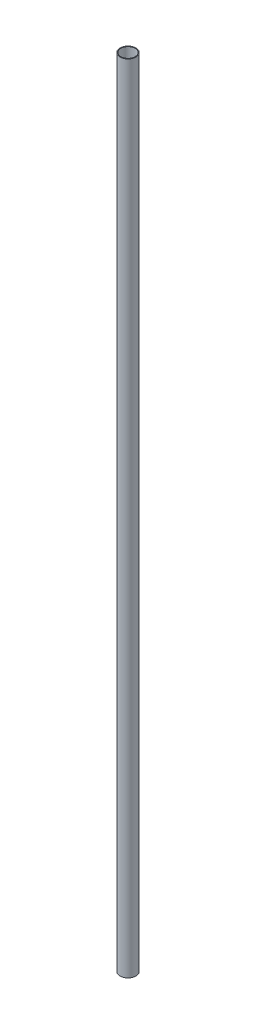
SolidWorks part; units mm, degrees
material "Thornel Mat VMA"
ref_plane "前视基准面" through (0, 0, 0) normal (0, 0, 1) x (1, 0, 0)
ref_plane "上视基准面" through (0, 0, 0) normal (0, 1, 0) x (1, 0, 0)
ref_plane "右视基准面" through (0, 0, 0) normal (1, 0, 0) x (0, 0, -1)
sketch "草图1" plane through (0, 0, 0) normal (0, 1, 0) x (1, 0, 0)
  circle A0 centre (0, 0) radius 10
  circle A1 centre (0, 0) radius 9
  dimension "D1" = 20
  dimension "D2" = 18
extrude "凸台-拉伸1" add sketch "草图1" along normal blind 1000
